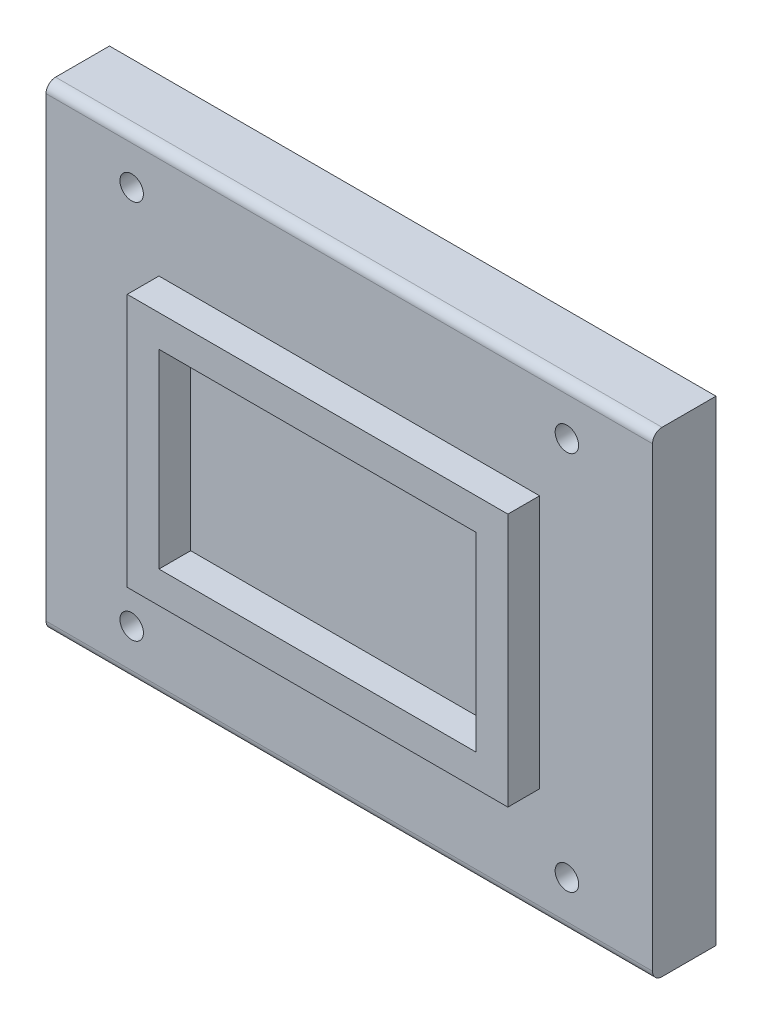
SolidWorks part; units mm, degrees
ref_plane "前基準面" through (0, 0, 0) normal (0, 0, 1) x (1, 0, 0)
ref_plane "上基準面" through (0, 0, 0) normal (0, 1, 0) x (1, 0, 0)
ref_plane "右基準面" through (0, 0, 0) normal (1, 0, 0) x (0, 0, -1)
sketch "草圖1" plane through (0, 0, 0) normal (0, 0, 1) x (1, 0, 0)
  line L1 (-39.4522, 17.6269) -> (56.1478, 17.6269)
  line L2 (-39.4522, 17.6269) -> (-39.4522, -57.3731)
  line L3 (-39.4522, -57.3731) -> (56.1478, -57.3731)
  line L4 (56.1478, 17.6269) -> (56.1478, -57.3731)
  circle A0 centre (-25.9522, 10.0769) radius 1.85
  circle A1 centre (42.6478, 10.0769) radius 1.85
  circle A2 centre (-25.9522, -49.8231) radius 1.85
  circle A3 centre (42.6478, -49.8231) radius 1.85
  dimension "D7" = 3.7
  dimension "D8" = 3.7
  dimension "D9" = 3.7
  dimension "D10" = 3.7
  dimension "D1" = 95.6
  dimension "D2" = 75
  dimension "D3" = 13.5
  dimension "D4" = 7.55
  dimension "D5" = 13.5
  dimension "D6" = 7.55
extrude "填料-伸長1" add sketch "草圖1" along normal blind 10
fillet "圓角1" radius 1.5 2 edges at (8.3478, -57.3731, 10) (8.3478, 17.6269, 10)
sketch "草圖2" plane through (0, 0, 10) normal (0, 0, 1) x (1, 0, 0)
  line L1 (-16.6522, -4.8731) -> (33.3478, -4.8731)
  line L2 (-16.6522, -4.8731) -> (-16.6522, -34.8731)
  line L3 (-16.6522, -34.8731) -> (33.3478, -34.8731)
  line L4 (33.3478, -4.8731) -> (33.3478, -34.8731)
  line L5 (-21.6522, 0.1269) -> (38.3478, 0.1269)
  line L6 (-21.6522, 0.1269) -> (-21.6522, -39.8731)
  line L7 (-21.6522, -39.8731) -> (38.3478, -39.8731)
  line L8 (38.3478, 0.1269) -> (38.3478, -39.8731)
  line L9 (-39.4522, 16.1269) -> (-39.4522, -55.8731) construction
  line L11 (56.1478, -57.3731) -> (-39.4522, -57.3731) construction
  dimension "D1" = 50
  dimension "D2" = 30
  dimension "D3" = 60
  dimension "D4" = 40
  dimension "D5" = 5
  dimension "D6" = 5
  dimension "D7" = 22.8
  dimension "D8" = 22.5
extrude "填料-伸長2" add sketch "草圖2" along normal blind 5
